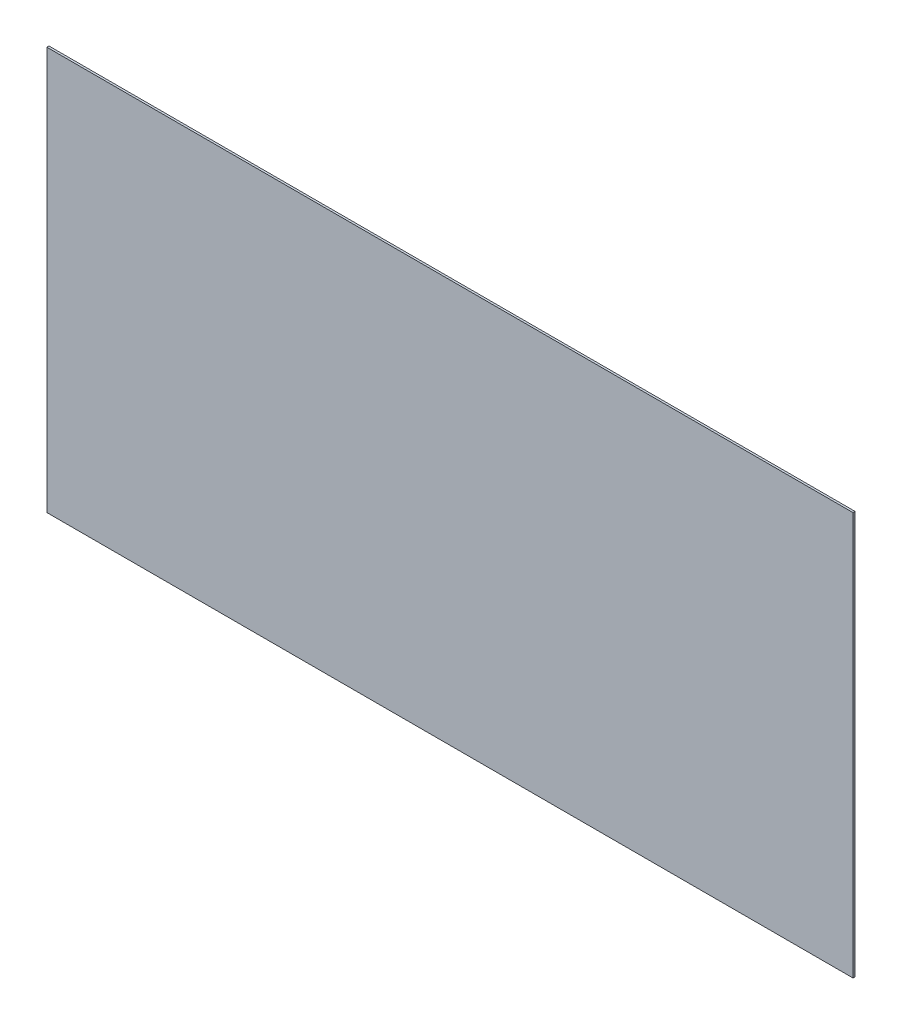
SolidWorks part; units mm, degrees
ref_plane "Front Plane" through (0, 0, 0) normal (0, 0, 1) x (1, 0, 0)
ref_plane "Top Plane" through (0, 0, 0) normal (0, 1, 0) x (1, 0, 0)
ref_plane "Right Plane" through (0, 0, 0) normal (1, 0, 0) x (0, 0, -1)
sketch "Sketch1" plane through (0, 0, 0) normal (0, 0, 1) x (1, 0, 0)
  line L1 (-304.8, -152.4) -> (304.8, -152.4)
  line L2 (-304.8, -152.4) -> (-304.8, 152.4)
  line L3 (-304.8, 152.4) -> (304.8, 152.4)
  line L4 (304.8, -152.4) -> (304.8, 152.4)
  line L5 (-304.8, -152.4) -> (304.8, 152.4) construction
  line L6 (-304.8, 152.4) -> (304.8, -152.4) construction
  point P0 (0, 0)
  dimension "D1" = 609.6
  dimension "D2" = 304.8
extrude "Boss-Extrude1" add sketch "Sketch1" along normal blind 1.5875
